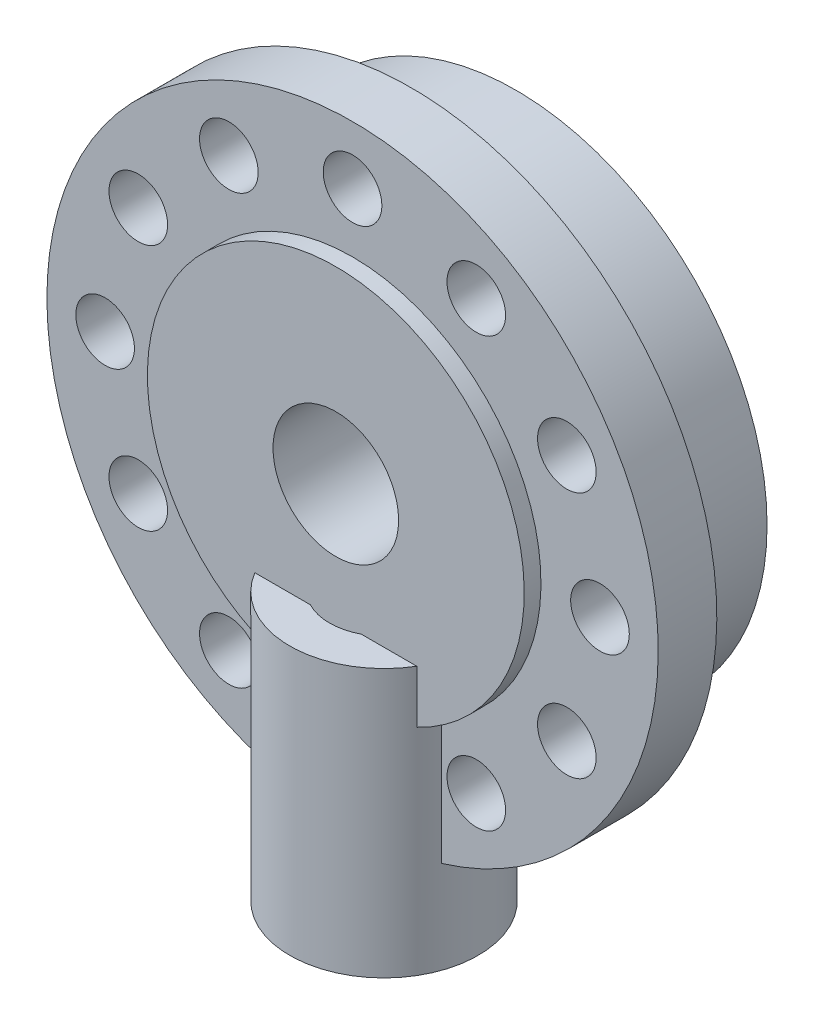
SolidWorks part; units mm, degrees
ref_plane "Front Plane" through (0, 0, 0) normal (0, 0, 1) x (1, 0, 0)
ref_plane "Top Plane" through (0, 0, 0) normal (0, 1, 0) x (1, 0, 0)
ref_plane "Right Plane" through (0, 0, 0) normal (1, 0, 0) x (0, 0, -1)
sketch "Sketch1" plane through (0, 0, 0) normal (0, 0, 1) x (1, 0, 0)
  circle A0 centre (0, 0) radius 60
extrude "Boss-Extrude1" add sketch "Sketch1" along normal blind 25
sketch "Sketch2" plane through (0, 0, 25) normal (0, 0, 1) x (1, 0, 0)
  circle A0 centre (0, 0) radius 73
extrude "Boss-Extrude2" add sketch "Sketch2" along normal blind 14
sketch "Sketch4" plane through (0, 0, 39) normal (0, 0, 1) x (1, 0, 0)
  circle A0 centre (0, 0) radius 45
extrude "Boss-Extrude3" add sketch "Sketch4" along normal blind 4
sketch "Sketch5" plane through (0, 0, 43) normal (0, 0, 1) x (1, 0, 0)
  circle A0 centre (0, 0) radius 15
extrude "Cut-Extrude1" cut sketch "Sketch5" against normal blind 99
sketch "Sketch6" plane through (0, 0, 39) normal (0, 0, 1) x (1, 0, 0)
  line L0 (0, 0) -> (0, 73) construction
  line L1 (0, 73) -> (0, 45.1903) construction
  circle A0 centre (0, 0) radius 73 construction
  circle A1 centre (0, 59.0951) radius 7
  circle A2 centre (29.5476, 51.1779) radius 7
  circle A3 centre (51.1779, 29.5476) radius 7
  circle A4 centre (59.0951, 0) radius 7
  circle A5 centre (51.1779, -29.5476) radius 7
  circle A6 centre (29.5476, -51.1779) radius 7
  circle A8 centre (-29.5476, -51.1779) radius 7
  circle A9 centre (-51.1779, -29.5476) radius 7
  circle A10 centre (-59.0951, 0) radius 7
  circle A11 centre (-51.1779, 29.5476) radius 7
  circle A12 centre (-29.5476, 51.1779) radius 7
  circle A13 centre (0, -59.0951) radius 7 [skipped]
  point P34 (0, 0)
  dimension "D1" = 12
extrude "Cut-Extrude2" cut sketch "Sketch6" against normal blind 10
ref_plane "Plane1" through (0, -73, 0) normal (0, -1, 0) x (-1, 0, 0)
sketch "Sketch7" plane through (0, -73, 0) normal (0, -1, 0) x (-1, 0, 0)
  line L0 (0, -62.9944) -> (0, 0) construction
  circle A0 centre (0, -31.4972) radius 13
  circle A1 centre (0, -31.4972) radius 22.5
extrude "Boss-Extrude4" add sketch "Sketch7" against normal blind 45 and the other way blind 19
